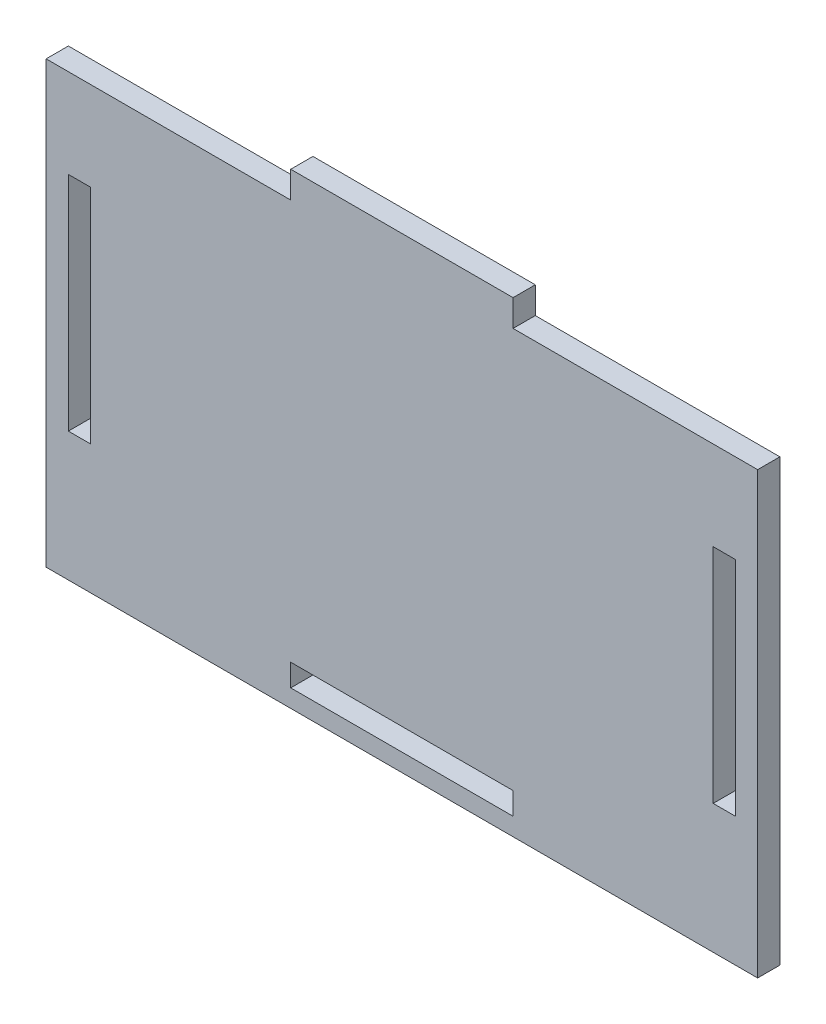
SolidWorks part; units mm, degrees
ref_plane "Front Plane" through (0, 0, 0) normal (0, 0, 1) x (1, 0, 0)
ref_plane "Top Plane" through (0, 0, 0) normal (0, 1, 0) x (1, 0, 0)
ref_plane "Right Plane" through (0, 0, 0) normal (1, 0, 0) x (0, 0, -1)
sketch "Sketch1" plane through (0, 0, 0) normal (0, 0, 1) x (1, 0, 0)
  line L0 (-44.45, 28.575) -> (-44.45, -34.29) construction
  line L1 (-50.8, 28.575) -> (-15.875, 28.575)
  line L2 (-50.8, 28.575) -> (-50.8, -34.29)
  line L3 (-50.8, -34.29) -> (50.8, -34.29)
  line L4 (50.8, 28.575) -> (50.8, -34.29)
  line L5 (44.45, 28.575) -> (44.45, -34.29) construction
  line L6 (-15.875, -28.575) -> (-50.8, -28.575) construction
  line L7 (-15.875, -28.575) -> (15.875, -28.575)
  line L8 (-15.875, -28.575) -> (-15.875, -31.75)
  line L9 (-15.875, -31.75) -> (15.875, -31.75)
  line L10 (15.875, -28.575) -> (15.875, -31.75)
  line L11 (15.875, -28.575) -> (50.8, -28.575) construction
  line L12 (15.875, 28.575) -> (50.8, 28.575)
  line L13 (0, 28.575) -> (0, -28.575) construction
  line L14 (-15.875, 28.575) -> (-15.875, 32.385)
  line L15 (-15.875, 32.385) -> (15.875, 32.385)
  line L16 (15.875, 28.575) -> (15.875, 32.385)
  line L17 (-47.625, 0) -> (47.625, 0) construction
  line L18 (0, -28.575) -> (0, -31.75) construction
  line L19 (-47.625, 0) -> (-44.45, 0) construction
  line L20 (-47.625, 15.875) -> (-44.45, 15.875)
  line L21 (-47.625, 15.875) -> (-47.625, -15.875)
  line L22 (-47.625, -15.875) -> (-44.45, -15.875)
  line L23 (-44.45, 15.875) -> (-44.45, -15.875)
  line L24 (44.45, 15.875) -> (47.625, 15.875)
  line L25 (44.45, 15.875) -> (44.45, -15.875)
  line L26 (44.45, -15.875) -> (47.625, -15.875)
  line L27 (47.625, 15.875) -> (47.625, -15.875)
  line L28 (47.625, 0) -> (44.45, 0) construction
  line L29 (-15.875, 28.575) -> (15.875, 28.575) construction
  dimension "D1" = 88.9
  dimension "D2" = 57.15
  dimension "D3" = 2.54
  dimension "D4" = 3.175
  dimension "D5" = 31.75
  dimension "D6" = 31.75
  dimension "D7" = 3.175
  dimension "D8" = 3.175
  dimension "D9" = 3.175
  dimension "D10" = 3.175
  dimension "D11" = 31.75
  dimension "D12" = 3.81
extrude "Boss-Extrude1" add sketch "Sketch1" along normal blind 3.175
